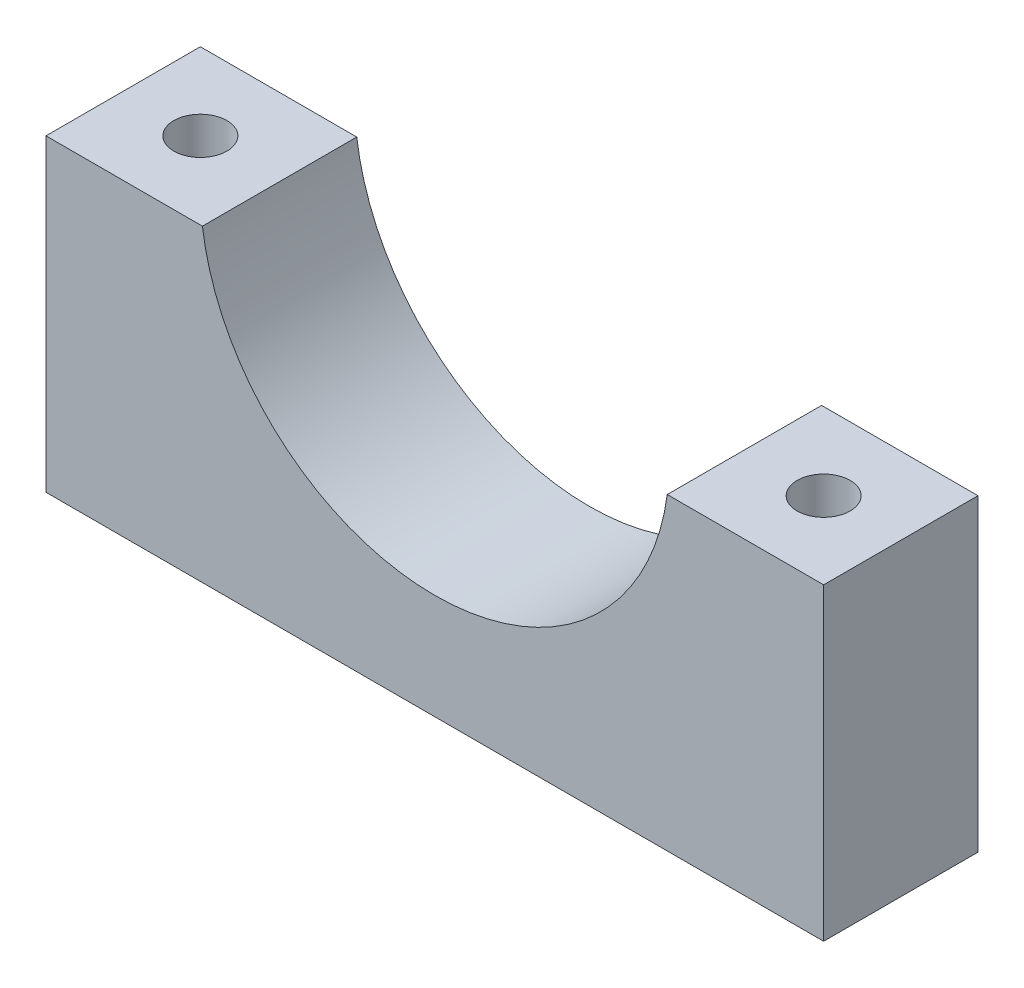
SolidWorks part; units mm, degrees
ref_plane "Front Plane" through (0, 0, 0) normal (0, 0, 1) x (1, 0, 0)
ref_plane "Top Plane" through (0, 0, 0) normal (0, 1, 0) x (1, 0, 0)
ref_plane "Right Plane" through (0, 0, 0) normal (1, 0, 0) x (0, 0, -1)
sketch "Sketch1" plane through (0, 0, 0) normal (0, 0, 1) x (1, 0, 0)
  line L0 (-31.9913, 0) -> (31.9913, 0) construction
  line L1 (-31.9913, 0) -> (-31.9913, -27.94) construction
  line L2 (-31.9913, 0) -> (31.9913, 0) construction
  line L3 (-31.9913, -27.94) -> (31.9913, -27.94) construction
  line L4 (31.9913, -27.94) -> (31.9913, 0) construction
  line L5 (-19.1234, -2.54) -> (-31.9913, -2.54)
  line L6 (-31.9913, -2.54) -> (-31.9913, -27.94)
  line L7 (-31.9913, -27.94) -> (31.9913, -27.94)
  line L8 (31.9913, -27.94) -> (31.9913, -2.54)
  line L9 (31.9913, -2.54) -> (19.1234, -2.54)
  line L10 (-31.9913, 0) -> (-19.2913, 0) construction
  circle A0 centre (0, 0) radius 19.2913 construction
  arc A1 (-19.1234, -2.54) -> (19.1234, -2.54) centre (0, 0) ccw
  point P6 (0, 0)
  point P14 (-31.9913, -9.0666)
  dimension "D1" = 38.5826
  dimension "D3" = 25.4
  dimension "D2" = 12.7
  dimension "D4" = 2.54
extrude "Boss-Extrude1" add sketch "Sketch1" along normal blind 12.7 contours L7 L8 L9 A1 L5 L6
sketch "Sketch2" plane through (0, -27.94, 0) normal (0, -1, 0) x (1, 0, 0)
  line L0 (-31.9913, 6.35) -> (31.9913, 6.35) construction
  line L3 (-31.9913, 12.7) -> (-31.9913, 0) construction
  line L4 (31.9913, 12.7) -> (31.9913, 0) construction
  circle A0 centre (-25.6413, 6.35) radius 2.1828
  circle A1 centre (25.6413, 6.35) radius 2.1828
  point P2 (-31.9018, 5.1929)
  point P4 (0, 0)
  point P10 (-31.9913, 6.35)
  point P13 (31.9913, 6.35)
  dimension "D1" = 6.35
  dimension "D2" = 6.35
extrude "Cut-Extrude1" cut sketch "Sketch2" against normal through all
